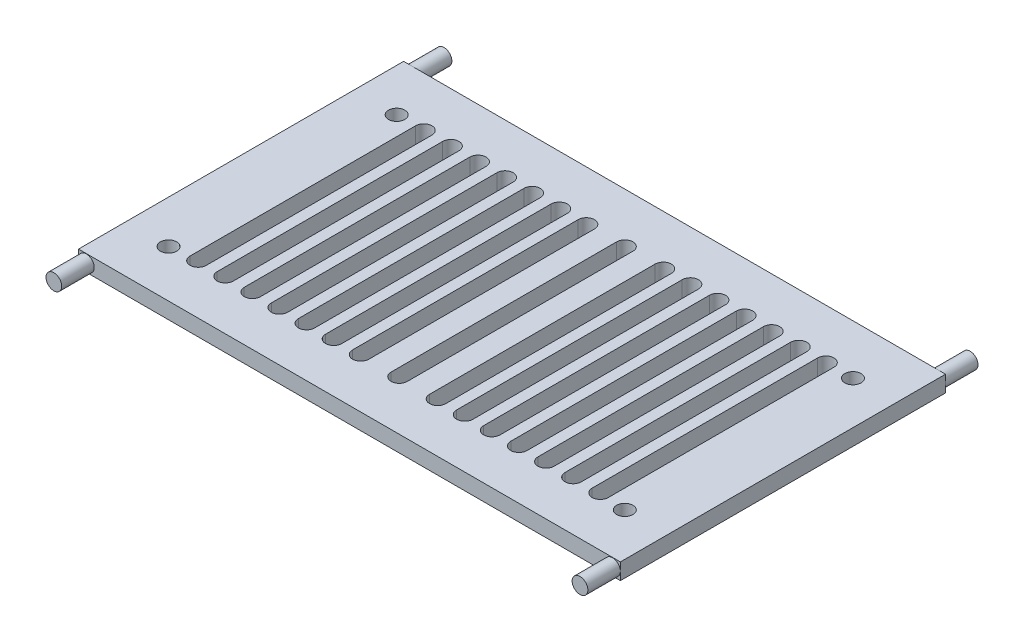
SolidWorks part; units mm, degrees
ref_plane "前视基准面" through (0, 0, 0) normal (0, 0, 1) x (1, 0, 0)
ref_plane "上视基准面" through (0, 0, 0) normal (0, 1, 0) x (1, 0, 0)
ref_plane "右视基准面" through (0, 0, 0) normal (1, 0, 0) x (0, 0, -1)
sketch "草图1" plane through (0, 0, 0) normal (0, 0, 1) x (1, 0, 0)
  line L6 (50, 0) -> (50, 1.5)
  line L7 (50, 1.5) -> (30, 1.5)
  line L8 (50, 0) -> (50, -1.5)
  line L9 (50, -1.5) -> (30, -1.5)
  line L11 (0, 1.5) -> (-50, 1.5)
  line L12 (-50, 1.5) -> (-50, -1.5)
  line L13 (-50, -1.5) -> (30, -1.5)
  line L14 (0, 1.5) -> (30, 1.5)
  dimension "D2" = 50
extrude "凸台-拉伸1" add sketch "草图1" along normal blind 55.815 and the other way blind 4.185
sketch "草图8" plane through (0, 1.5, 0) normal (0, 1, 0) x (1, 0, 0)
  line L0 (0, 6.5636) -> (0, -58.1936) construction
  line L1 (-42.1, -5) -> (-37.1, -5) construction
  line L2 (1.5, -5) -> (1.5, -46.63)
  line L3 (0, 0) -> (0, -5)
  line L4 (-37.1, -5) -> (-32.1, -5) construction
  line L5 (-32.1, -5) -> (-27.1, -5) construction
  line L6 (-27.1, -5) -> (-22.1, -5) construction
  line L7 (-22.1, -5) -> (-17.1, -5) construction
  line L8 (-17.1, -5) -> (-12.1, -5) construction
  line L9 (-12.1, -5) -> (-7.1, -5) construction
  line L10 (-7.1, -5) -> (0, -5) construction
  line L11 (-55.9521, -25.815) -> (52.7009, -25.815) construction
  line L12 (-38.6, -5) -> (-38.6, -46.63)
  line L13 (-35.6, -5) -> (-35.6, -46.63)
  line L14 (-33.6, -5) -> (-33.6, -46.63)
  line L15 (-30.6, -5) -> (-30.6, -46.63)
  line L16 (-28.6, -5) -> (-28.6, -46.63)
  line L17 (-25.6, -5) -> (-25.6, -46.63)
  line L18 (-23.6, -5) -> (-23.6, -46.63)
  line L19 (-20.6, -5) -> (-20.6, -46.63)
  line L20 (-18.6, -5) -> (-18.6, -46.63)
  line L21 (-15.6, -5) -> (-15.6, -46.63)
  line L22 (-13.6, -5) -> (-13.6, -46.63)
  line L23 (-10.6, -5) -> (-10.6, -46.63)
  line L24 (-8.6, -5) -> (-8.6, -46.63)
  line L25 (-5.6, -5) -> (-5.6, -46.63)
  line L26 (-7.1, -46.63) -> (0, -46.63) construction
  line L27 (-12.1, -46.63) -> (-7.1, -46.63) construction
  line L28 (-17.1, -46.63) -> (-12.1, -46.63) construction
  line L29 (-22.1, -46.63) -> (-17.1, -46.63) construction
  line L30 (-27.1, -46.63) -> (-22.1, -46.63) construction
  line L31 (-32.1, -46.63) -> (-27.1, -46.63) construction
  line L32 (-37.1, -46.63) -> (-32.1, -46.63) construction
  line L33 (-42.1, -46.63) -> (-37.1, -46.63) construction
  line L34 (37.1, -46.63) -> (32.1, -46.63) construction
  line L35 (32.1, -46.63) -> (27.1, -46.63) construction
  line L36 (27.1, -46.63) -> (22.1, -46.63) construction
  line L37 (12.1, -5) -> (7.1, -5) construction
  line L38 (17.1, -5) -> (12.1, -5) construction
  line L39 (22.1, -5) -> (17.1, -5) construction
  line L40 (27.1, -5) -> (22.1, -5) construction
  line L41 (32.1, -5) -> (27.1, -5) construction
  line L42 (37.1, -5) -> (32.1, -5) construction
  line L43 (5.6, -5) -> (5.6, -46.63)
  line L44 (8.6, -5) -> (8.6, -46.63)
  line L45 (10.6, -5) -> (10.6, -46.63)
  line L46 (13.6, -5) -> (13.6, -46.63)
  line L47 (15.6, -5) -> (15.6, -46.63)
  line L48 (18.6, -5) -> (18.6, -46.63)
  line L49 (20.6, -5) -> (20.6, -46.63)
  line L50 (23.6, -5) -> (23.6, -46.63)
  line L51 (25.6, -5) -> (25.6, -46.63)
  line L52 (28.6, -5) -> (28.6, -46.63)
  line L53 (30.6, -5) -> (30.6, -46.63)
  line L54 (33.6, -5) -> (33.6, -46.63)
  line L55 (35.6, -5) -> (35.6, -46.63)
  line L56 (38.6, -5) -> (38.6, -46.63)
  line L57 (22.1, -46.63) -> (17.1, -46.63) construction
  line L58 (17.1, -46.63) -> (12.1, -46.63) construction
  line L59 (12.1, -46.63) -> (7.1, -46.63) construction
  line L60 (-1.5, -5) -> (-1.5, -46.63)
  circle A0 centre (-42.1, -5) radius 1.5
  circle A1 centre (-42.1, -47.1) radius 1.5
  circle A2 centre (42.1, -47.1) radius 1.5
  circle A3 centre (42.1, -5) radius 1.5
  arc A11 (-38.6, -5) -> (-35.6, -5) centre (-37.1, -5) cw
  arc A12 (-33.6, -5) -> (-30.6, -5) centre (-32.1, -5) cw
  arc A13 (-28.6, -5) -> (-25.6, -5) centre (-27.1, -5) cw
  arc A14 (-23.6, -5) -> (-20.6, -5) centre (-22.1, -5) cw
  arc A15 (-18.6, -5) -> (-15.6, -5) centre (-17.1, -5) cw
  arc A16 (-13.6, -5) -> (-10.6, -5) centre (-12.1, -5) cw
  arc A17 (-8.6, -5) -> (-5.6, -5) centre (-7.1, -5) cw
  arc A18 (-8.6, -46.63) -> (-5.6, -46.63) centre (-7.1, -46.63) ccw
  arc A19 (-13.6, -46.63) -> (-10.6, -46.63) centre (-12.1, -46.63) ccw
  arc A20 (-18.6, -46.63) -> (-15.6, -46.63) centre (-17.1, -46.63) ccw
  arc A21 (-23.6, -46.63) -> (-20.6, -46.63) centre (-22.1, -46.63) ccw
  arc A22 (-28.6, -46.63) -> (-25.6, -46.63) centre (-27.1, -46.63) ccw
  arc A23 (-33.6, -46.63) -> (-30.6, -46.63) centre (-32.1, -46.63) ccw
  arc A24 (-38.6, -46.63) -> (-35.6, -46.63) centre (-37.1, -46.63) ccw
  arc A25 (38.6, -46.63) -> (35.6, -46.63) centre (37.1, -46.63) cw
  arc A26 (33.6, -46.63) -> (30.6, -46.63) centre (32.1, -46.63) cw
  arc A27 (28.6, -46.63) -> (25.6, -46.63) centre (27.1, -46.63) cw
  arc A28 (23.6, -46.63) -> (20.6, -46.63) centre (22.1, -46.63) cw
  arc A29 (8.6, -5) -> (5.6, -5) centre (7.1, -5) ccw
  arc A30 (13.6, -5) -> (10.6, -5) centre (12.1, -5) ccw
  arc A31 (18.6, -5) -> (15.6, -5) centre (17.1, -5) ccw
  arc A32 (23.6, -5) -> (20.6, -5) centre (22.1, -5) ccw
  arc A33 (28.6, -5) -> (25.6, -5) centre (27.1, -5) ccw
  arc A34 (33.6, -5) -> (30.6, -5) centre (32.1, -5) ccw
  arc A35 (38.6, -5) -> (35.6, -5) centre (37.1, -5) ccw
  arc A36 (18.6, -46.63) -> (15.6, -46.63) centre (17.1, -46.63) cw
  arc A37 (13.6, -46.63) -> (10.6, -46.63) centre (12.1, -46.63) cw
  arc A38 (8.6, -46.63) -> (5.6, -46.63) centre (7.1, -46.63) cw
  arc A40 (1.5, -5) -> (-1.5, -5) centre (0, -5) ccw
  arc A41 (1.5, -46.63) -> (-1.5, -46.63) centre (0, -46.63) cw
  point P32 (-38.6, -25.815)
  point P34 (-35.6, -25.815)
  point P36 (-33.6, -25.815)
  point P38 (-30.6, -25.815)
  point P40 (-28.6, -25.815)
  point P42 (-25.6, -25.815)
  point P44 (-23.6, -25.815)
  point P46 (-20.6, -25.815)
  point P48 (-18.6, -25.815)
  point P50 (-15.6, -25.815)
  point P52 (-13.6, -25.815)
  point P54 (-10.6, -25.815)
  point P56 (-8.6, -25.815)
  point P75 (-5.6, -25.815)
  point P114 (23.6, -25.815)
  point P115 (25.6, -25.815)
  point P116 (28.6, -25.815)
  point P117 (30.6, -25.815)
  point P118 (33.6, -25.815)
  point P119 (35.6, -25.815)
  point P120 (38.6, -25.815)
  point P124 (5.6, -25.815)
  point P125 (8.6, -25.815)
  point P126 (10.6, -25.815)
  point P127 (13.6, -25.815)
  point P128 (15.6, -25.815)
  point P129 (18.6, -25.815)
  point P130 (20.6, -25.815)
  point P133 (1.5, -25.815)
  point P136 (-1.5, -25.815)
  dimension "D4" = 3
  dimension "D5" = 3
  dimension "D11" = 5
  dimension "D13" = 1.5
  dimension "D1" = 5
  dimension "D2" = 42.1
  dimension "D3" = 42.1
  dimension "D6" = 5
  dimension "D7" = 5
  dimension "D8" = 5
  dimension "D9" = 5
  dimension "D10" = 5
  dimension "D12" = 5
extrude "切除-拉伸1" cut sketch "草图8" against normal blind 3
sketch "草图11" plane through (0, 0, 55.815) normal (0, 0, 1) x (1, 0, 0)
  line L0 (-50, 0) -> (-48.55, 0) construction
  line L2 (-50, 1.5) -> (-50, -1.5) construction
  line L3 (0, 3.7959) -> (0, -4.3783) construction
  circle A0 centre (-48.55, 0) radius 1.45
  circle A1 centre (48.55, 0) radius 1.45
  dimension "D2" = 97.1
  dimension "D3" = 2.9
  dimension "D1" = 1.45
extrude "凸台-拉伸4" add sketch "草图11" along normal blind 6
sketch "草图12" plane through (0, 0, -4.185) normal (0, 0, -1) x (-1, 0, 0)
  line L0 (0, 3.9664) -> (0, -2.6602)
  circle A0 centre (-48.55, 0) radius 1.45
  circle A1 centre (48.55, 0) radius 1.45
extrude "凸台-拉伸5" add sketch "草图12" along normal blind 6 contours A0 | A1
